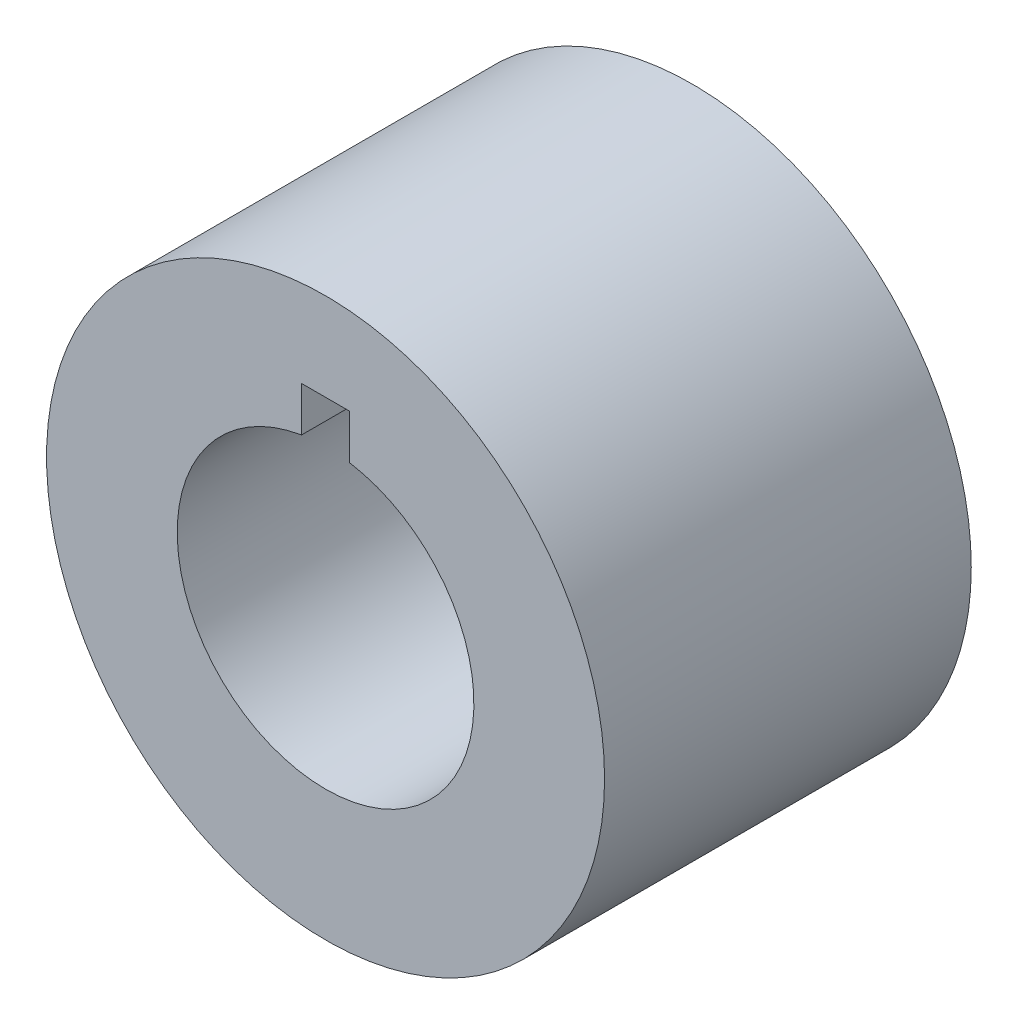
SolidWorks part; units mm, degrees
ref_plane "Front Plane" through (0, 0, 0) normal (0, 0, 1) x (1, 0, 0)
ref_plane "Top Plane" through (0, 0, 0) normal (0, 1, 0) x (1, 0, 0)
ref_plane "Right Plane" through (0, 0, 0) normal (1, 0, 0) x (0, 0, -1)
sketch "Sketch1" plane through (0, 0, 0) normal (0, 0, 1) x (1, 0, 0)
  line L0 (0, 17.653) -> (0, 13.5255) construction
  line L1 (-2.2225, 17.653) -> (2.2225, 17.653)
  line L2 (-2.2225, 17.653) -> (-2.2225, 13.5255)
  line L4 (2.2225, 17.653) -> (2.2225, 13.5255)
  arc A0 (-2.2225, 13.5255) -> (2.2225, 13.5255) centre (0, 0) ccw
  circle A1 centre (0, 0) radius 25.781
  dimension "D5" = 51.562
  dimension "D1" = 4.445
  dimension "D2" = 4.1275
  dimension "D3" = 17.653
  dimension "D4" = 0
extrude "Boss-Extrude1" add sketch "Sketch1" along normal blind 33.8836
